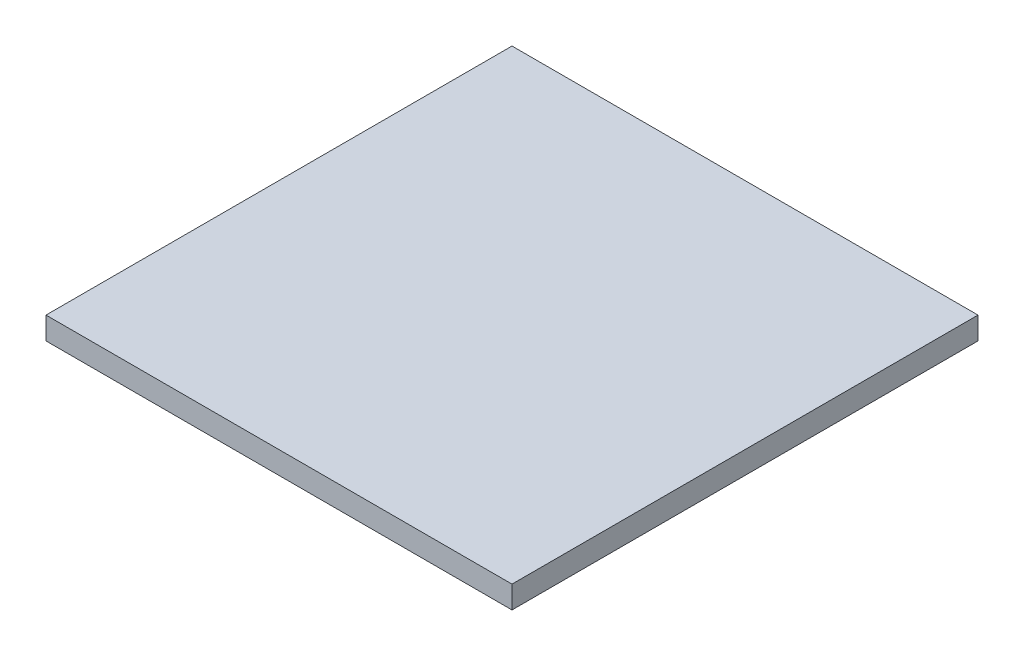
SolidWorks part; units mm, degrees
material "Rubber"
ref_plane "Front Plane" through (0, 0, 0) normal (0, 0, 1) x (1, 0, 0)
ref_plane "Top Plane" through (0, 0, 0) normal (0, 1, 0) x (1, 0, 0)
ref_plane "Right Plane" through (0, 0, 0) normal (1, 0, 0) x (0, 0, -1)
sketch "Sketch1" plane through (0, 0, 0) normal (0, 1, 0) x (1, 0, 0)
  line L1 (0, 0) -> (104, 0)
  line L2 (0, 0) -> (0, 104)
  line L3 (0, 104) -> (104, 104)
  line L4 (104, 0) -> (104, 104)
  dimension "D1" = 104
  dimension "D2" = 104
extrude "Boss-Extrude1" add sketch "Sketch1" along normal blind 5
